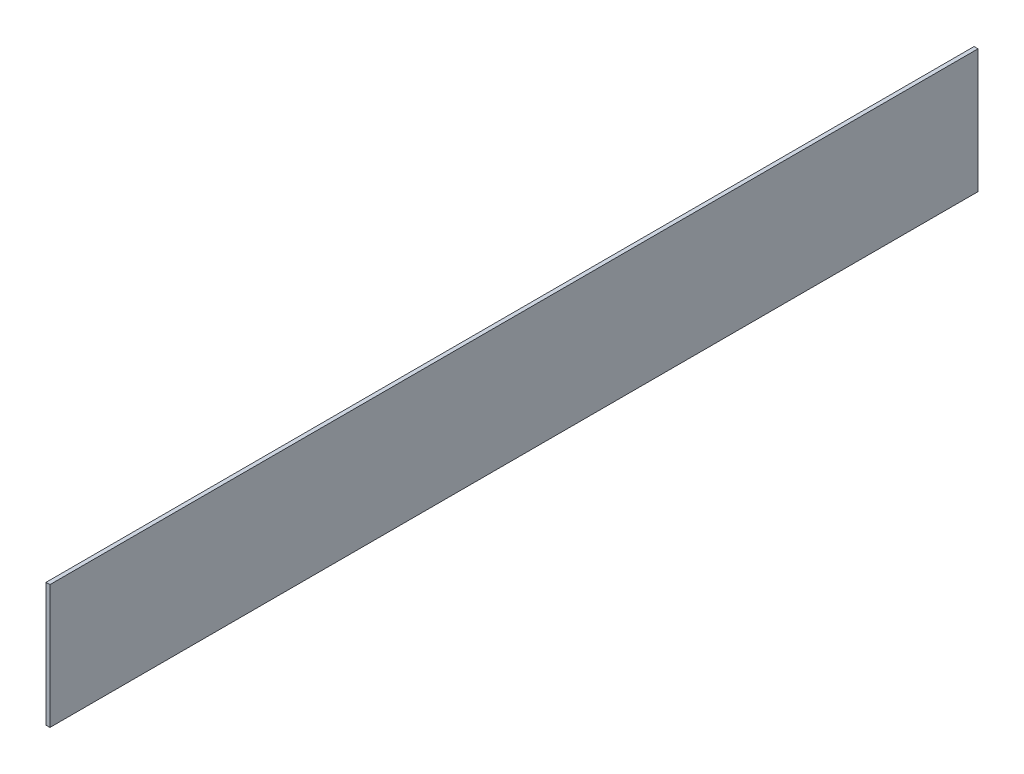
SolidWorks part; units mm, degrees
ref_plane "Front Plane" through (0, 0, 0) normal (0, 0, 1) x (1, 0, 0)
ref_plane "Top Plane" through (0, 0, 0) normal (0, 1, 0) x (1, 0, 0)
ref_plane "Right Plane" through (0, 0, 0) normal (1, 0, 0) x (0, 0, -1)
sketch "Sketch1" plane through (0, 0, 0) normal (1, 0, 0) x (0, 0, -1)
  line L1 (750, 100) -> (-750, 100)
  line L2 (750, 100) -> (750, -100)
  line L3 (750, -100) -> (-750, -100)
  line L4 (-750, 100) -> (-750, -100)
  line L5 (750, 100) -> (-750, -100) construction
  line L6 (750, -100) -> (-750, 100) construction
  point P0 (0, 0)
  dimension "D1" = 200
  dimension "D2" = 1500
extrude "Boss-Extrude1" add sketch "Sketch1" along normal mid plane 6.35
